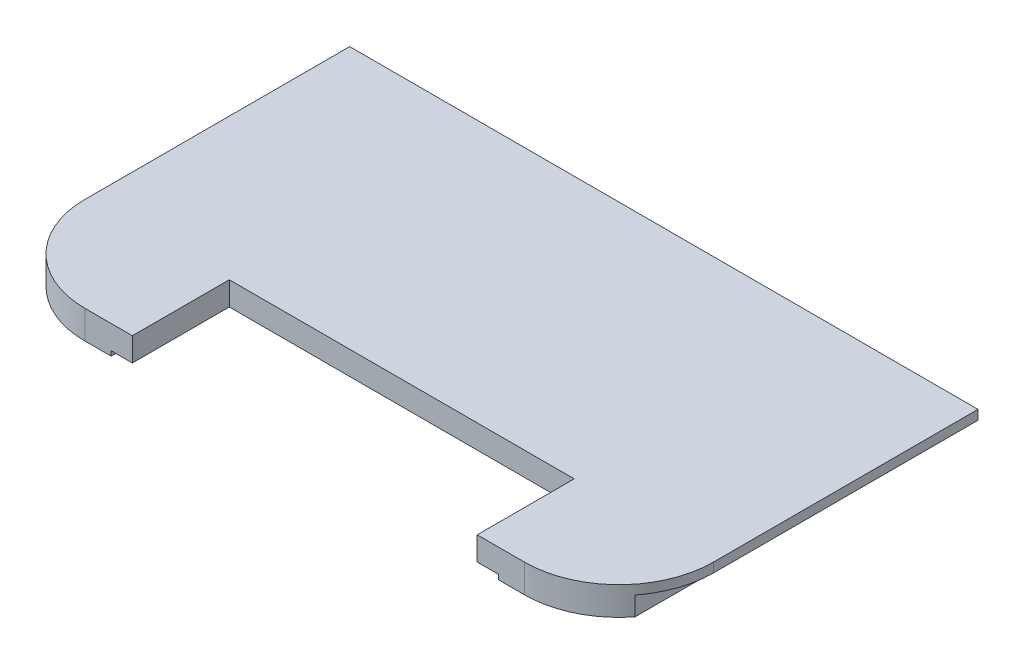
SolidWorks part; units mm, degrees
material "MDF"
ref_plane "Front Plane" through (0, 0, 0) normal (0, 0, 1) x (1, 0, 0)
ref_plane "Top Plane" through (0, 0, 0) normal (0, 1, 0) x (1, 0, 0)
ref_plane "Right Plane" through (0, 0, 0) normal (1, 0, 0) x (0, 0, -1)
sketch "Sketch1" plane through (0, 0, 0) normal (0, 1, 0) x (1, 0, 0)
  line L1 (-211.1375, -120.65) -> (211.1375, -120.65)
  line L2 (-211.1375, -120.65) -> (-211.1375, 120.65)
  line L3 (-211.1375, 120.65) -> (211.1375, 120.65)
  line L4 (211.1375, -120.65) -> (211.1375, 120.65)
  line L5 (-211.1375, -120.65) -> (211.1375, 120.65) construction
  line L6 (-211.1375, 120.65) -> (211.1375, -120.65) construction
  point P0 (0, 0)
  dimension "D1" = 422.275
  dimension "D2" = 241.3
extrude "Boss-Extrude1" add sketch "Sketch1" along normal blind 19.05
sketch "Sketch2" plane through (0, 19.05, 0) normal (0, 1, 0) x (1, 0, 0)
  line L0 (-211.1375, -120.65) -> (211.1375, -120.65) construction
  line L1 (-115.8875, -120.65) -> (115.8875, -120.65)
  line L2 (-115.8875, -120.65) -> (-115.8875, -55.499)
  line L3 (-115.8875, -55.499) -> (115.8875, -55.499)
  line L4 (115.8875, -120.65) -> (115.8875, -55.499)
  line L5 (0, 120.65) -> (0, -176.45) construction
  line L6 (211.1375, 120.65) -> (-211.1375, 120.65) construction
  line L7 (0, -10.4775) -> (0, 10.4775) construction
  line L8 (-211.1375, 120.65) -> (-211.1375, -120.65) construction
  dimension "D1" = 95.25
  dimension "D2" = 65.151
  dimension "D3" = 231.775
extrude "Cut-Extrude1" cut sketch "Sketch2" against normal up to next
sketch "Sketch3" plane through (0, 0, 120.65) normal (0, 0, 1) x (1, 0, 0)
  line L1 (-115.8875, 0) -> (-130.175, 0)
  line L2 (-115.8875, 0) -> (-115.8875, 3.175)
  line L3 (-115.8875, 3.175) -> (-130.175, 3.175)
  line L4 (-130.175, 0) -> (-130.175, 3.175)
  line L5 (115.8875, 0) -> (130.175, 0)
  line L6 (115.8875, 0) -> (115.8875, 3.175)
  line L7 (115.8875, 3.175) -> (130.175, 3.175)
  line L8 (130.175, 0) -> (130.175, 3.175)
  dimension "D1" = 3.175
  dimension "D2" = 14.2875
extrude "Cut-Extrude2" cut sketch "Sketch3" against normal up to next
sketch "Sketch4" plane through (0, 0, 120.65) normal (0, 0, 1) x (1, 0, 0)
  line L0 (130.175, 3.175) -> (115.8875, 3.175) construction
  line L1 (-211.1375, 0) -> (-197.6438, 0)
  line L2 (-211.1375, 0) -> (-211.1375, 3.175)
  line L3 (-211.1375, 3.175) -> (-197.6438, 3.175)
  line L4 (-197.6438, 0) -> (-197.6438, 3.175)
  line L5 (211.1375, 0) -> (197.6437, 0)
  line L6 (211.1375, 0) -> (211.1375, 3.175)
  line L7 (211.1375, 3.175) -> (197.6437, 3.175)
  line L8 (197.6437, 0) -> (197.6437, 3.175)
  line L9 (-115.8875, 3.175) -> (-130.175, 3.175) construction
  dimension "D1" = 13.4937
extrude "Cut-Extrude3" cut sketch "Sketch4" against normal up to next
fillet "Fillet1" radius 63.5 2 edges at (211.1375, 11.1125, 120.65) (-211.1375, 11.1125, 120.65)
sketch "Sketch5" plane through (0, 0, -120.65) normal (0, 0, -1) x (-1, 0, 0)
  line L0 (-211.1375, 19.05) -> (-211.1375, 3.175) construction
  line L1 (-197.6437, 3.175) -> (-211.1375, 3.175)
  line L2 (-197.6437, 3.175) -> (-197.6437, 12.7)
  line L3 (-197.6437, 12.7) -> (-211.1375, 12.7)
  line L4 (-211.1375, 3.175) -> (-211.1375, 12.7)
  line L5 (197.6438, 3.175) -> (197.6438, 0) construction
  line L6 (211.1375, 3.175) -> (197.6438, 3.175)
  line L7 (211.1375, 3.175) -> (211.1375, 12.7)
  line L8 (211.1375, 12.7) -> (197.6438, 12.7)
  line L9 (197.6438, 3.175) -> (197.6438, 12.7)
  line L10 (132.715, 0) -> (-132.715, 0) construction
  dimension "D1" = 12.7
extrude "Cut-Extrude4" cut sketch "Sketch5" against normal up to next
chamfer "Chamfer1" distance 3.175 angle 75 1 edges at (0, 0, 55.499)
